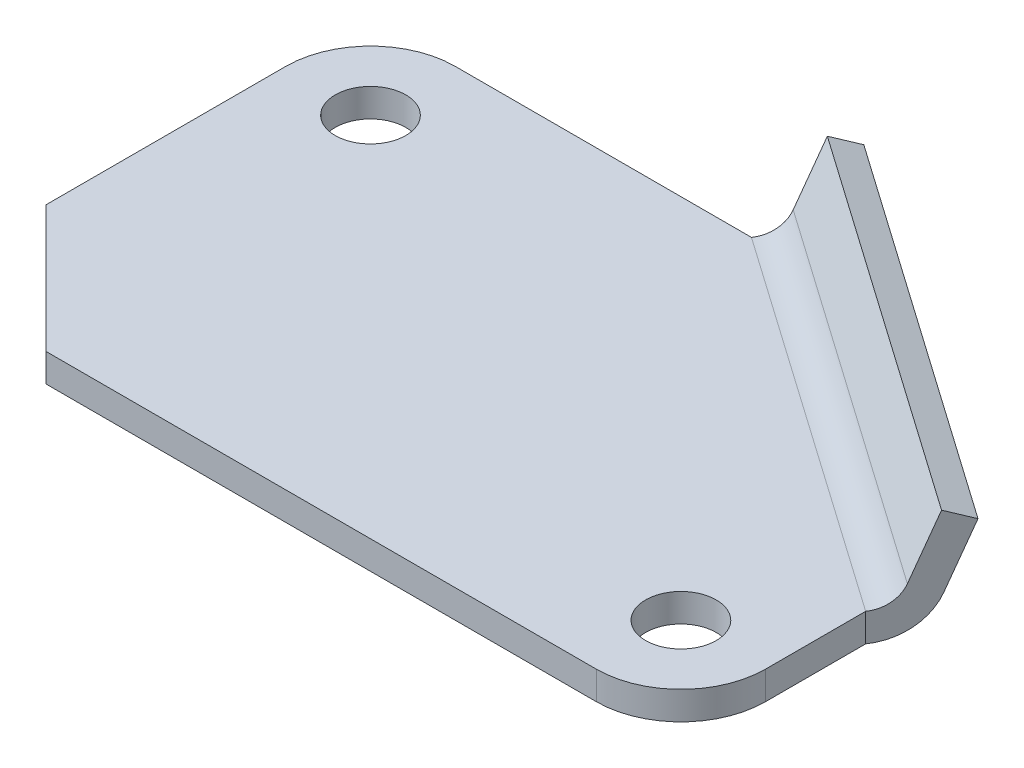
SolidWorks part; units mm, degrees
ref_plane "Front Plane" through (0, 0, 0) normal (0, 0, 1) x (1, 0, 0)
ref_plane "Top Plane" through (0, 0, 0) normal (0, 1, 0) x (1, 0, 0)
ref_plane "Right Plane" through (0, 0, 0) normal (1, 0, 0) x (0, 0, -1)
sketch "Sketch2" plane through (0, 0, 0) normal (0, 1, 0) x (1, 0, 0)
  line L0 (0, 18) -> (18, 0)
  line L1 (18, 0) -> (96, 0)
  line L2 (0, 18) -> (0, 52)
  line L3 (12, 64) -> (54, 64)
  line L4 (108, 12) -> (108, 26.1888)
  line L5 (54, 64) -> (108, 26.1888)
  arc A0 (12, 64) -> (0, 52) centre (12, 52) ccw
  circle A1 centre (12, 52) radius 5
  arc A2 (96, 0) -> (108, 12) centre (96, 12) ccw
  circle A3 centre (96, 12) radius 5
  point P0 (0, 0)
  point P1 (108, 64)
  dimension "D1" = 10
  dimension "D2" = 24
  dimension "D5" = 24
  dimension "D6" = 10
  dimension "D3" = 64
  dimension "D4" = 108
  dimension "D7" = 54
  dimension "D8" = 35
extrude "Boss-Extrude2" add sketch "Sketch2" along normal blind 4
ref_plane "Plane1" through (6.1644, 0, 4.3163) normal (0.8192, 0, 0.5736) x (0.5736, 0, -0.8192)
sketch "Sketch6" plane through (6.1644, 0, 4.3163) normal (0.8192, 0, 0.5736) x (0.5736, 0, -0.8192)
  line L0 (91.3564, 5.3674) -> (94.8329, 13.972)
  line L1 (71.7761, 0) -> (83.3989, 0) construction
  line L2 (71.7761, 4) -> (83.3989, 4) construction
  line L3 (87.6477, 6.8659) -> (91.1242, 15.4704)
  line L4 (94.8329, 13.972) -> (91.1242, 15.4704)
  line L5 (83.3989, 0) -> (83.3989, 4)
  arc A0 (83.3989, 0) -> (91.3564, 5.3674) centre (83.3989, 8.5825) ccw
  arc A1 (83.3989, 4) -> (87.6477, 6.8659) centre (83.3989, 8.5825) ccw
  dimension "D1" = 112
  dimension "D2" = 4
extrude "Boss-Extrude3" add sketch "Sketch6" along normal up to vertex (65.9218 mm away)
